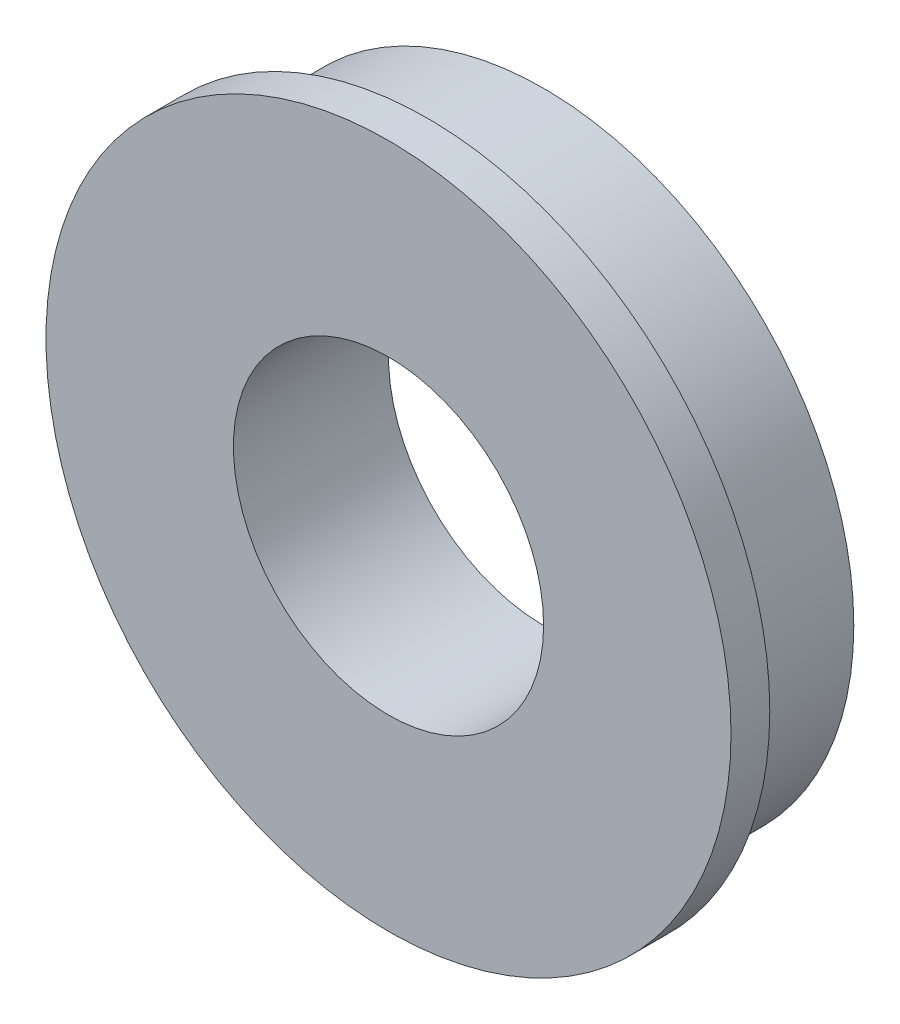
SolidWorks part; units mm, degrees
material "ｽﾃﾝﾚｽ鋼(ｸﾛﾑ)"
ref_plane "正面" through (0, 0, 0) normal (0, 0, 1) x (1, 0, 0)
ref_plane "平面" through (0, 0, 0) normal (0, 1, 0) x (1, 0, 0)
ref_plane "右側面" through (0, 0, 0) normal (1, 0, 0) x (0, 0, -1)
sketch "ｽｹｯﾁ1" plane through (0, 0, 0) normal (0, 0, 1) x (1, 0, 0)
  circle A0 centre (-22, 0) radius 12
extrude "押し出し1" add sketch "ｽｹｯﾁ1" against normal blind 4.5
sketch "ｽｹｯﾁ2" plane through (0, 0, 0) normal (0, 0, 1) x (1, 0, 0)
  circle A0 centre (-22, 0) radius 13.25
  dimension "D1" = 26.5
extrude "押し出し2" add sketch "ｽｹｯﾁ2" along normal blind 1.5
sketch "ｽｹｯﾁ3" plane through (0, 0, 1.5) normal (0, 0, 1) x (1, 0, 0)
  circle A0 centre (-22, 0) radius 6
  dimension "D1" = 12
extrude "ｶｯﾄ - 押し出し1" cut sketch "ｽｹｯﾁ3" against normal through all
